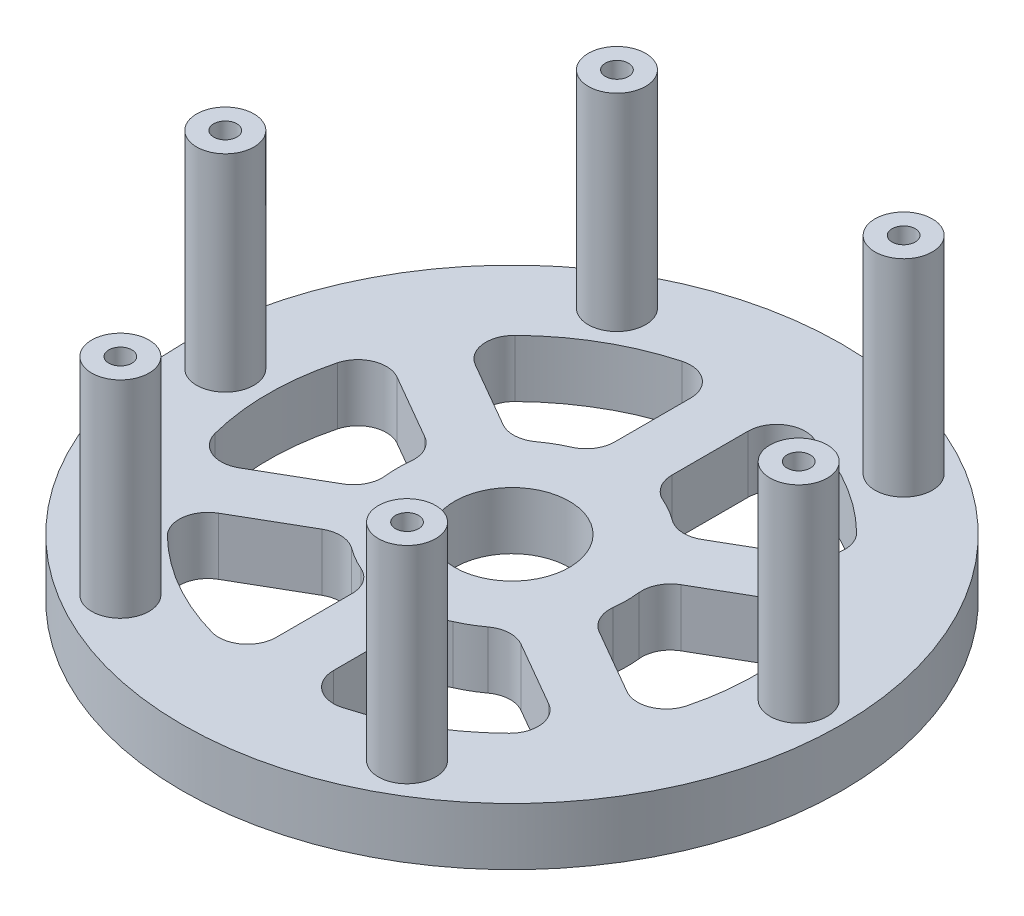
SolidWorks part; units mm, degrees
ref_plane "Front Plane" through (0, 0, 0) normal (0, 0, 1) x (1, 0, 0)
ref_plane "Top Plane" through (0, 0, 0) normal (0, 1, 0) x (1, 0, 0)
ref_plane "Right Plane" through (0, 0, 0) normal (1, 0, 0) x (0, 0, -1)
sketch "Sketch1" plane through (0, 0, 0) normal (0, 1, 0) x (1, 0, 0)
  line L0 (0, 10) -> (0, 20) construction
  line L1 (0, 57.5) -> (0, 42.5)
  circle A0 centre (0, 0) radius 20
  circle A1 centre (0, 0) radius 10
  circle A2 centre (0, 0) radius 57.5
  circle A3 centre (0, 0) radius 42.5
  dimension "D1" = 40
  dimension "D2" = 10
  dimension "D3" = 115
  dimension "D4" = 15
extrude "Boss-Extrude1" add sketch "Sketch1" along normal mid plane 10
sketch "Sketch2" plane through (0, -5, 0) normal (0, -1, 0) x (1, 0, 0)
  line L0 (-5, 10) -> (-5, 42.5)
  line L1 (-5, 42.5) -> (5, 42.5)
  line L2 (5, 42.5) -> (5, 10)
  line L3 (5, 10) -> (-5, 10)
  circle A0 centre (0, 0) radius 10 construction
  circle A1 centre (0, 0) radius 42.5 construction
  point P5 (0, 10)
  dimension "D1" = 10
extrude "Boss-Extrude2" add sketch "Sketch2" against normal up to surface (10 mm away) up to face at (0, 5, 42.5)
sketch "Sketch3" plane through (0, -5, 0) normal (0, -1, 0) x (1, 0, 0)
  circle A0 centre (0, 0) radius 50 construction
  point P3 (50, 0)
  dimension "D1" = 100
sketch "Sketch4" plane through (0, 5, 0) normal (0, 1, 0) x (1, 0, 0)
  circle A0 centre (50, 0) radius 5
  dimension "D1" = 10
extrude "Boss-Extrude3" add sketch "Sketch4" along normal blind 36
hole_wizard "Tap Drill for #10-32 Tap1" positions "Sketch5" profile "Sketch6" hole size "#10-32" standard "ANSI Inch" end condition up to next
sketch "Sketch5" plane through (0, -5, 0) normal (0, -1, 0) x (-1, 0, 0)
  point P0 (-50, 0)
sketch "Sketch6" plane through (50, -5, 0) normal (1, 0, 0) x (0, 0, -1)
  line L0 (0, 0) -> (0, 46)
  line L1 (0, 46) -> (2.0193, 46)
  line L2 (2.0193, 46) -> (2.0193, 0)
  line L5 (2.0193, 0) -> (0, 0)
  line L11 (0, -6.35) -> (0, 107.95) construction
  dimension "Thru Hole Dia." = 4.0386
  dimension "Thru Hole Depth" = 46
fillet "Fillet1" radius 5 4 edges at (-5, 0, 42.2049) (-5, 0, 19.3649) (5, 0, 42.2049) (5, 0, 19.3649)
pattern_circular "CirPattern1" count 6 over 360 about axis through (0, 0, 0) along (0, 1, 0) of "Boss-Extrude2", "Fillet1", "Boss-Extrude3", "Tap Drill for #10-32 Tap1"
equation "\"GEARDIST\"=26.62"
